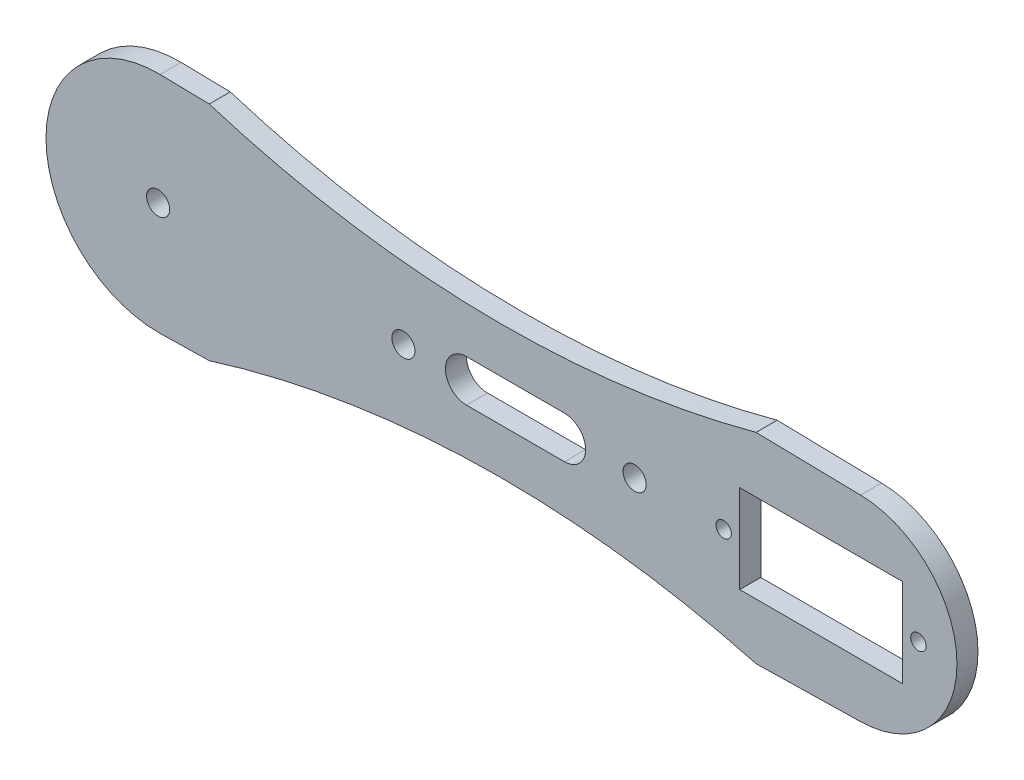
SolidWorks part; units mm, degrees
ref_plane "Спереди" through (0, 0, 0) normal (0, 0, 1) x (1, 0, 0)
ref_plane "Сверху" through (0, 0, 0) normal (0, 1, 0) x (1, 0, 0)
ref_plane "Справа" through (0, 0, 0) normal (1, 0, 0) x (0, 0, -1)
other "Configuration Table"
sketch "Eskiz_kontur" plane through (0, 0, 0) normal (0, 0, 1) x (1, 0, 0)
  line L0 (7.2912, -15.8573) -> (0.2792, -15.9976)
  line L1 (100.2443, -13.9979) -> (85.3309, -14.2962)
  line L2 (0.2792, 15.9976) -> (7.2912, 15.8573)
  line L3 (85.3309, 14.2962) -> (100.2443, 13.9979)
  line L4 (58, 3) -> (44, 3)
  line L5 (44, -3) -> (58, -3)
  line L6 (106.2, -6.3) -> (106.2, 6.3)
  line L7 (106.2, 6.3) -> (83, 6.3)
  line L8 (83, -6.3) -> (106.2, -6.3)
  line L9 (83, 6.3) -> (83, -6.3)
  arc A0 (85.3309, -14.2962) -> (7.2912, -15.8573) centre (49, -149.5) ccw
  arc A1 (0.2792, -15.9976) -> (0.2792, 15.9976) centre (0, 0) cw
  arc A2 (100.2443, 13.9979) -> (100.2443, -13.9979) centre (99.9999, 0) cw
  arc A3 (7.2912, 15.8573) -> (85.3309, 14.2962) centre (49, 149.5) ccw
  arc A4 (44, 3) -> (44, -3) centre (44, 0) ccw
  arc A5 (58, -3) -> (58, 3) centre (58, 0) ccw
extrude "Plastina" add sketch "Eskiz_kontur" along normal blind 3
sketch "Eskiz_otverstiya" plane through (0, 0, 0) normal (0, 0, 1) x (1, 0, 0)
  circle A0 centre (0, 0) radius 1.65
  circle A1 centre (35, 0) radius 1.65
  circle A2 centre (68, 0) radius 1.65
  circle A3 centre (80.7, 0) radius 1.1
  circle A4 centre (108.5, 0) radius 1.1
  dimension "d1" = 3.3
  dimension "d2" = 3.3
  dimension "d3" = 3.3
  dimension "d4" = 2.2
  dimension "d5" = 2.2
extrude "Otverstiya" cut sketch "Eskiz_otverstiya" against normal through all and the other way through all
equation "\"T3\" = 3"
equation "\"T5\" = 5"
equation "\"D_M3\" = 3.3"
equation "\"D_M2\" = 2.2"
equation "\"D_M3_TAP\" = 2.5"
equation "\"D_M4\" = 4.5"
equation "\"L1\" = 100"
equation "\"L2\" = 100"
equation "\"D1@Plastina\" = \"T3\""
equation "\"d1@Eskiz_otverstiya\" = \"D_M3\""
equation "\"d2@Eskiz_otverstiya\" = \"D_M3\""
equation "\"d3@Eskiz_otverstiya\" = \"D_M3\""
equation "\"d4@Eskiz_otverstiya\" = \"D_M2\""
equation "\"d5@Eskiz_otverstiya\" = \"D_M2\""
